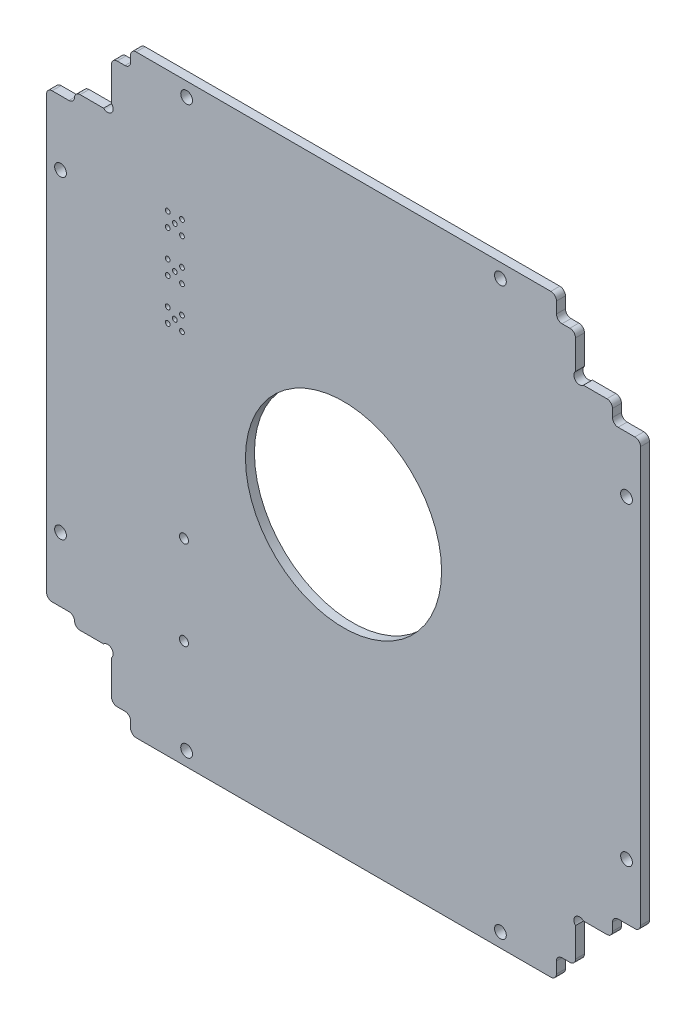
SolidWorks part; units mm, degrees
ref_plane "Front Plane" through (0, 0, 0) normal (0, 0, 1) x (1, 0, 0)
ref_plane "Top Plane" through (0, 0, 0) normal (0, 1, 0) x (1, 0, 0)
ref_plane "Right Plane" through (0, 0, 0) normal (1, 0, 0) x (0, 0, -1)
sketch "Sketch1" plane through (0, 0, 0) normal (0, 0, 1) x (1, 0, 0)
  line L0 (53, 53) -> (-53, -53) construction
  line L1 (53, 53) -> (-53, 53)
  line L2 (53, 53) -> (53, -53)
  line L3 (53, -53) -> (-53, -53)
  line L4 (-53, 53) -> (-53, -53)
  point P4 (0, 0)
  dimension "D1" = 106
  dimension "D2" = 106
extrude "mainOutline" add sketch "Sketch1" along normal blind 1.6
sketch "axisLabels" plane through (0, 0, 0) normal (0, 0, -1) x (-1, 0, 0)
  text T0 "+Y"
  text T1 "+X"
sketch "Sketch4" plane through (0, 0, 0) normal (0, 0, -1) x (-1, 0, 0)
  line L1 (-41.4, -41.4) -> (-48, -41.4)
  line L3 (-41.4, -49) -> (-41.4, -41.4)
  line L5 (-60.1065, -39) -> (-49.9975, -39)
  line L7 (-39, -61.4521) -> (-39, -49.9)
  line L9 (39, -56.2753) -> (39, -49.9)
  line L10 (-53, 53) -> (53, 53) construction
  line L11 (41.4, -49.9) -> (41.4, -41.4)
  line L12 (-53, -53) -> (-53, 53) construction
  line L13 (41.4, -41.4) -> (48, -41.4)
  line L15 (48, -40.5) -> (55.5177, -40.5)
  line L17 (55.3838, 40.5) -> (48, 40.5)
  line L19 (39, 57.6877) -> (39, 49.9)
  line L21 (-39, 59.8804) -> (-39, 49.9)
  line L23 (-56.8428, 39) -> (-49.9975, 39)
  line L25 (-41.4, 41.4) -> (-41.4, 49)
  line L27 (-48, 41.4) -> (-41.4, 41.4)
  line L29 (41.4, 49.9) -> (41.4, 41.4)
  line L31 (48, 41.4) -> (41.4, 41.4)
  line L32 (-48, 41.4) -> (-48, 39)
  line L33 (-48, 39) -> (-49.9975, 39)
  line L34 (-41.4, 49) -> (-39, 49)
  line L35 (-39, 49) -> (-39, 49.9)
  line L36 (48, 40.5) -> (48, 41.4)
  line L37 (39, 49.9) -> (41.4, 49.9)
  line L38 (48, -40.5) -> (48, -41.4)
  line L39 (39, -49.9) -> (41.4, -49.9)
  line L40 (-41.4, -49) -> (-39, -49)
  line L41 (-39, -49) -> (-39, -49.9)
  line L42 (-49.9975, -39) -> (-48, -39)
  line L43 (-48, -39) -> (-48, -41.4)
  line L44 (-39, 59.8804) -> (-56.8428, 59.8804)
  line L45 (-56.8428, 59.8804) -> (-56.8428, 39)
  line L46 (53, 53) -> (53, -53) construction
  line L47 (-60.1065, -39) -> (-60.1065, -61.4521)
  line L48 (-60.1065, -61.4521) -> (-39, -61.4521)
  line L49 (39, -56.2753) -> (55.5177, -56.2753)
  line L50 (55.5177, -56.2753) -> (55.5177, -40.5)
  line L51 (55.3838, 40.5) -> (55.3838, 57.6877)
  line L52 (55.3838, 57.6877) -> (39, 57.6877)
  line L53 (53, -53) -> (-53, -53) construction
  dimension "D1" = 14
  dimension "D2" = 11.6
  dimension "D3" = 5
  dimension "D4" = 12.5
  dimension "D5" = 11.6
  dimension "D6" = 3.1
  dimension "D7" = 12.5
  dimension "D8" = 14
  dimension "D9" = 3.1
  dimension "D10" = 5
  dimension "D11" = 11.6
  dimension "D12" = 11.6
  dimension "D13" = 14
  dimension "D14" = 14
  dimension "D15" = 11.6
  dimension "D16" = 11.6
  dimension "D17" = 5
  dimension "D18" = 4
  dimension "D19" = 14
  dimension "D20" = 14
  dimension "D21" = 11.6
  dimension "D22" = 11.6
  dimension "D23" = 4
  dimension "D24" = 5
extrude "railCutouts" cut sketch "Sketch4" against normal through all
sketch "Sketch5" plane through (0, 0, 0) normal (0, 0, -1) x (-1, 0, 0)
  line L0 (-48.7071, -39.7071) -> (-52.4015, -43.4015) construction
  line L1 (-48, -40.4142) -> (-51.6944, -44.1086) construction
  line L2 (-49.4142, -39) -> (-53.1086, -42.6944) construction
  line L3 (-48, -41.4) -> (-48, -39) construction
  line L4 (-48, 39) -> (-48, 41.4) construction
  line L5 (-42.1071, -42.1071) -> (-45.4445, -45.4445) construction
  line L6 (-41.4, -42.8142) -> (-44.7374, -46.1516)
  line L7 (-42.8142, -41.4) -> (-46.1516, -44.7374)
  line L8 (-39.7071, -49.7071) -> (-42.6199, -52.6199) construction
  line L9 (-39, -50.4142) -> (-41.9128, -53.327) construction
  line L10 (-40.4142, -49) -> (-43.327, -51.9128) construction
  line L11 (39.7071, -50.6071) -> (41.4231, -52.3231) construction
  line L12 (40.4142, -49.9) -> (42.1302, -51.616) construction
  line L13 (39, -51.3142) -> (40.716, -53.0302) construction
  line L14 (42.1071, -42.1071) -> (44.0402, -44.0402) construction
  line L15 (42.8142, -41.4) -> (44.7473, -43.3331)
  line L16 (41.4, -42.8142) -> (43.3331, -44.7473)
  line L17 (48.7071, -41.2071) -> (49.9793, -42.4793) construction
  line L18 (49.4142, -40.5) -> (50.6865, -41.7722) construction
  line L19 (48, -41.9142) -> (49.2722, -43.1865) construction
  line L20 (48.7071, 41.2071) -> (50.5001, 43.0001) construction
  line L21 (48, 41.9142) -> (49.793, 43.7072) construction
  line L22 (49.4142, 40.5) -> (51.2072, 42.293) construction
  line L23 (42.1071, 42.1071) -> (44.029, 44.029) construction
  line L24 (41.4, 42.8142) -> (43.3219, 44.7361)
  line L25 (42.8142, 41.4) -> (44.7361, 43.3219)
  line L26 (39.7071, 50.6071) -> (41.2638, 52.1638) construction
  line L27 (39, 51.3142) -> (40.5567, 52.8709) construction
  line L28 (40.4142, 49.9) -> (41.9709, 51.4567) construction
  line L29 (-48.7071, 39.7071) -> (-50.0606, 41.0606) construction
  line L30 (-49.4142, 39) -> (-50.7677, 40.3535) construction
  line L31 (-48, 40.4142) -> (-49.3535, 41.7677) construction
  line L32 (-42.1071, 42.1071) -> (-43.7968, 43.7968) construction
  line L33 (-42.8142, 41.4) -> (-44.5039, 43.0897)
  line L34 (-41.4, 42.8142) -> (-43.0897, 44.5039)
  line L35 (-39.7071, 49.7071) -> (-41.256, 51.256) construction
  line L36 (-40.4142, 49) -> (-41.9631, 50.5489) construction
  line L37 (-39, 50.4142) -> (-40.5489, 51.9631) construction
  line L38 (-41.4, 41.4) -> (-41.4, 49) construction
  line L39 (-39, 49) -> (-39, 53) construction
  line L40 (39, 53) -> (39, 49.9) construction
  line L41 (41.4, 49.9) -> (41.4, 41.4) construction
  line L42 (48, 41.4) -> (48, 40.5) construction
  line L43 (39, -49.9) -> (39, -53) construction
  line L44 (41.4, -41.4) -> (41.4, -49.9) construction
  line L45 (53, -40.5) -> (48, -40.5) construction
  line L46 (-39, -53) -> (-39, -49) construction
  line L47 (-41.4, -49) -> (-41.4, -41.4) construction
  arc A0 (-48, -40.4142) -> (-49.4142, -39) centre (-48.7071, -39.7071) ccw construction
  arc A1 (-53.1086, -42.6944) -> (-51.6944, -44.1086) centre (-52.4015, -43.4015) ccw construction
  arc A2 (-41.4, -42.8142) -> (-42.8142, -41.4) centre (-42.1071, -42.1071) ccw
  arc A3 (-46.1516, -44.7374) -> (-44.7374, -46.1516) centre (-45.4445, -45.4445) ccw
  arc A4 (-39, -50.4142) -> (-40.4142, -49) centre (-39.7071, -49.7071) ccw construction
  arc A5 (-43.327, -51.9128) -> (-41.9128, -53.327) centre (-42.6199, -52.6199) ccw construction
  arc A6 (40.4142, -49.9) -> (39, -51.3142) centre (39.7071, -50.6071) ccw construction
  arc A7 (40.716, -53.0302) -> (42.1302, -51.616) centre (41.4231, -52.3231) ccw construction
  arc A8 (42.8142, -41.4) -> (41.4, -42.8142) centre (42.1071, -42.1071) ccw
  arc A9 (43.3331, -44.7473) -> (44.7473, -43.3331) centre (44.0402, -44.0402) ccw
  arc A10 (49.4142, -40.5) -> (48, -41.9142) centre (48.7071, -41.2071) ccw construction
  arc A11 (49.2722, -43.1865) -> (50.6865, -41.7722) centre (49.9793, -42.4793) ccw construction
  arc A12 (48, 41.9142) -> (49.4142, 40.5) centre (48.7071, 41.2071) ccw construction
  arc A13 (51.2072, 42.293) -> (49.793, 43.7072) centre (50.5001, 43.0001) ccw construction
  arc A14 (41.4, 42.8142) -> (42.8142, 41.4) centre (42.1071, 42.1071) ccw
  arc A15 (44.7361, 43.3219) -> (43.3219, 44.7361) centre (44.029, 44.029) ccw
  arc A16 (39, 51.3142) -> (40.4142, 49.9) centre (39.7071, 50.6071) ccw construction
  arc A17 (41.9709, 51.4567) -> (40.5567, 52.8709) centre (41.2638, 52.1638) ccw construction
  arc A18 (-49.4142, 39) -> (-48, 40.4142) centre (-48.7071, 39.7071) ccw construction
  arc A19 (-49.3535, 41.7677) -> (-50.7677, 40.3535) centre (-50.0606, 41.0606) ccw construction
  arc A20 (-42.8142, 41.4) -> (-41.4, 42.8142) centre (-42.1071, 42.1071) ccw
  arc A21 (-43.0897, 44.5039) -> (-44.5039, 43.0897) centre (-43.7968, 43.7968) ccw
  arc A22 (-40.4142, 49) -> (-39, 50.4142) centre (-39.7071, 49.7071) ccw construction
  arc A23 (-40.5489, 51.9631) -> (-41.9631, 50.5489) centre (-41.256, 51.256) ccw construction
  point P2 (-50.5543, -41.5543)
  point P9 (-43.7758, -43.7758)
  point P17 (-41.1635, -51.1635)
  point P24 (40.5651, -51.4651)
  point P31 (43.0736, -43.0736)
  point P38 (49.3432, -41.8432)
  point P45 (49.6036, 42.1036)
  point P52 (43.0681, 43.0681)
  point P59 (40.4855, 51.3855)
  point P66 (-49.3839, 40.3839)
  point P73 (-42.952, 42.952)
  point P80 (-40.4815, 50.4815)
  dimension "D2" = 1
  dimension "D1" = 45
  dimension "D3" = 45
  dimension "D4" = 45
  dimension "D5" = 45
  dimension "D6" = 45
  dimension "D7" = 45
  dimension "D8" = 45
  dimension "D9" = 45
  dimension "D10" = 45
  dimension "D11" = 45
  dimension "D12" = 45
  dimension "D13" = 45
extrude "dogbones" cut sketch "Sketch5" against normal through all
sketch "Sketch6" plane through (0, 0, 0) normal (0, 0, -1) x (-1, 0, 0)
  line L0 (-39, 50) -> (-39, 53) construction
  line L1 (-39, 49) -> (-39, 53) construction
  line L2 (-39, 53) -> (39, 53) construction
  line L3 (-40, 50) -> (-40, 53)
  line L4 (-38, 50) -> (-38, 53)
  line L5 (-49, 39) -> (-53, 39) construction
  line L6 (-53, 39) -> (-48, 39) construction
  line L7 (-49, 38) -> (-53, 38)
  line L8 (-49, 40) -> (-53, 40)
  line L9 (-49, -39) -> (-55.2142, -39) construction
  line L10 (-48, -39) -> (-53, -39) construction
  line L11 (-49, -40) -> (-55.2142, -40)
  line L12 (-49, -38) -> (-55.2142, -38)
  line L13 (-39, -50) -> (-39, -53.9161) construction
  line L14 (-39, -53) -> (-39, -49) construction
  line L15 (-38, -50) -> (-38, -53.9161)
  line L16 (-40, -50) -> (-40, -53.9161)
  line L17 (39, -50.9) -> (39, -54.538) construction
  line L18 (39, -49.9) -> (39, -53) construction
  line L19 (40, -50.9) -> (40, -54.538)
  line L20 (38, -50.9) -> (38, -54.538)
  line L21 (49, -40.5) -> (54.2026, -40.5) construction
  line L22 (53, -40.5) -> (48, -40.5) construction
  line L23 (49, -39.5) -> (54.2026, -39.5)
  line L24 (49, -41.5) -> (54.2026, -41.5)
  line L25 (49, 40.5) -> (54.5566, 40.5) construction
  line L26 (48, 40.5) -> (53, 40.5) construction
  line L27 (49, 41.5) -> (54.5566, 41.5)
  line L28 (49, 39.5) -> (54.5566, 39.5)
  line L29 (39, 50.9) -> (39, 55.8281) construction
  line L30 (39, 53) -> (39, 49.9) construction
  line L31 (38, 50.9) -> (38, 55.8281)
  line L32 (40, 50.9) -> (40, 55.8281)
  line L33 (-48, -41.4) -> (-48, -39) construction
  line L34 (-39, -49) -> (-41.4, -49) construction
  line L35 (41.4, -49.9) -> (39, -49.9) construction
  line L36 (48, -40.5) -> (48, -41.4) construction
  line L37 (48, 41.4) -> (48, 40.5) construction
  line L38 (39, 49.9) -> (41.4, 49.9) construction
  arc A0 (-40, 50) -> (-38, 50) centre (-39, 50) ccw
  arc A1 (-38, 53) -> (-40, 53) centre (-39, 53) ccw
  arc A2 (-49, 38) -> (-49, 40) centre (-49, 39) ccw
  arc A3 (-53, 40) -> (-53, 38) centre (-53, 39) ccw
  arc A4 (-49, -40) -> (-49, -38) centre (-49, -39) ccw
  arc A5 (-55.2142, -38) -> (-55.2142, -40) centre (-55.2142, -39) ccw
  arc A6 (-38, -50) -> (-40, -50) centre (-39, -50) ccw
  arc A7 (-40, -53.9161) -> (-38, -53.9161) centre (-39, -53.9161) ccw
  arc A8 (40, -50.9) -> (38, -50.9) centre (39, -50.9) ccw
  arc A9 (38, -54.538) -> (40, -54.538) centre (39, -54.538) ccw
  arc A10 (49, -39.5) -> (49, -41.5) centre (49, -40.5) ccw
  arc A11 (54.2026, -41.5) -> (54.2026, -39.5) centre (54.2026, -40.5) ccw
  arc A12 (49, 41.5) -> (49, 39.5) centre (49, 40.5) ccw
  arc A13 (54.5566, 39.5) -> (54.5566, 41.5) centre (54.5566, 40.5) ccw
  arc A14 (38, 50.9) -> (40, 50.9) centre (39, 50.9) ccw
  arc A15 (40, 55.8281) -> (38, 55.8281) centre (39, 55.8281) ccw
  point P6 (-39, 51.5)
  point P11 (-51, 39)
  point P21 (-52.1071, -39)
  point P30 (-39, -51.958)
  point P39 (39, -52.719)
  point P48 (51.6013, -40.5)
  point P57 (51.7783, 40.5)
  point P66 (39, 53.364)
  point P75 (-39, 49)
  dimension "D1" = 1
extrude "solarFillets" cut sketch "Sketch6" against normal through all
fillet "handlingFillets" radius 1 16 edges at (-41.4, -49.9, 0.8) (-38, -53, 0.8) (-53, -39.5, 0.8) (-48, -41.4, 0.8) (-48, 41.4, 0.8) (-53, 39.5, 0.8) (-41.4, 49.9, 0.8) (-38, 53, 0.8) (38, 53, 0.8) (41.4, 49, 0.8) (48, 41.4, 0.8) (53, 38, 0.8) (53, -38, 0.8) (48, -41.4, 0.8) (41.4, -49, 0.8) (38, -53, 0.8)
sketch "Sketch7" plane through (0, 0, 1.6) normal (0, 0, 1) x (1, 0, 0)
  line L0 (-37, -53) -> (37, -53) construction
  line L1 (-53, 38.5) -> (-53, -38.5) construction
  line L2 (37, 53) -> (-37, 53) construction
  line L3 (-31.37, 28.67) -> (-31.37, 31.21) construction
  line L4 (-31.37, 31.21) -> (-28.83, 31.21) construction
  line L5 (-28.83, 31.21) -> (-28.83, 28.67) construction
  line L6 (-28.83, 28.67) -> (-31.37, 28.67) construction
  line L7 (-31.37, 28.67) -> (-28.83, 31.21) construction
  circle A1 centre (-28.4723, -17.925) radius 0.8
  circle A3 centre (-28.4723, -33.775) radius 0.8
  circle A5 centre (-31.37, 28.67) radius 0.425
  circle A7 centre (-28.83, 28.67) radius 0.425
  circle A9 centre (-30.1, 29.94) radius 0.425
  circle A10 centre (-28.83, 31.21) radius 0.425
  circle A11 centre (-31.37, 31.21) radius 0.425
  circle A12 centre (-31.37, 21.27) radius 0.425
  circle A13 centre (-28.83, 21.27) radius 0.425
  circle A14 centre (-30.1, 22.54) radius 0.425
  circle A15 centre (-28.83, 23.81) radius 0.425
  circle A16 centre (-31.37, 23.81) radius 0.425
  circle A17 centre (-31.37, 13.87) radius 0.425
  circle A18 centre (-28.83, 13.87) radius 0.425
  circle A19 centre (-30.1, 15.14) radius 0.425
  circle A20 centre (-28.83, 16.41) radius 0.425
  circle A21 centre (-31.37, 16.41) radius 0.425
  point P13 (-30.1, 29.94)
  dimension "D8" = 1.6
  dimension "D9" = 3
  dimension "D6" = 0.85
  dimension "D1" = 19.225
  dimension "D2" = 24.5277
  dimension "D3" = 15.85
  dimension "D4" = 23.06
  dimension "D5" = 22.9
  dimension "D7" = 2.54
  dimension "D10" = 7.4
extrude "connectorHoles" cut sketch "Sketch7" against normal through all
hole_wizard "M2 Clearance Hole1" positions "Sketch8" profile "Sketch9" hole size "M2" standard "ANSI Metric" end condition through all
sketch "Sketch8" plane through (0, 0, 0) normal (0, 0, -1) x (-1, 0, 0)
  line L0 (53, 38.5) -> (53, -38.5) construction
  line L1 (37, -53) -> (-37, -53) construction
  line L2 (-53, -37) -> (-53, 37) construction
  line L3 (53, 0) -> (-53, 0) construction
  line L5 (0, -53) -> (0, -11.6379) construction
  point P0 (50.5, -28)
  point P1 (28, -50.5)
  point P5 (-50.5, -28)
  point P30 (-28, -50.5)
  point P31 (-28, 50.5)
  point P32 (-50.5, 28)
  point P33 (28, 50.5)
  point P34 (50.5, 28)
  dimension "D1" = 2.5
  dimension "D2" = 2.5
  dimension "D4" = 2.5
  dimension "D5" = 25
  dimension "D6" = 25
  dimension "D7" = 25
sketch "Sketch9" plane through (-50.5, -28, 0) normal (1, 0, 0) x (0, 1, 0)
  line L0 (0, 0) -> (0, 1.6)
  line L1 (0, 1.6) -> (1.05, 1.6)
  line L2 (1.05, 1.6) -> (1.05, 0)
  line L5 (1.05, 0) -> (0, 0)
  line L11 (0, -6.35) -> (0, 107.95) construction
  dimension "Thru Hole Dia." = 2.1
  dimension "Thru Hole Depth" = 1.6
sketch "Sketch10" plane through (0, 0, 0) normal (0, 0, -1) x (-1, 0, 0)
  line L0 (-41.4, -45.4071) -> (41.4, -45.4071) construction
  line L1 (-41.4, -48) -> (-41.4, -42.8142) construction
  line L2 (41.4, -42.8142) -> (41.4, -48.9) construction
  line L3 (44.9084, -41.4) -> (44.9084, 41.4) construction
  line L4 (47.0025, -41.4) -> (42.8142, -41.4) construction
  line L5 (42.8142, 41.4) -> (47.0025, 41.4) construction
  line L6 (-41.4, 45.4071) -> (41.4, 45.4071) construction
  line L7 (-41.4, 42.8142) -> (-41.4, 48) construction
  line L8 (41.4, 48.9) -> (41.4, 42.8142) construction
  line L9 (-44.9071, 41.4) -> (-44.9071, -41.4) construction
  line L10 (-47, 41.4) -> (-42.8142, 41.4) construction
  line L11 (-42.8142, -41.4) -> (-47, -41.4) construction
  line L12 (-44.9071, 0) -> (44.9084, 0) construction
  line L13 (0, 45.4071) -> (0, -45.4071) construction
  circle A0 centre (0, 0) radius 17.5
  dimension "D1" = 35
extrude "Cut-Extrude1" cut sketch "Sketch10" against normal through all
